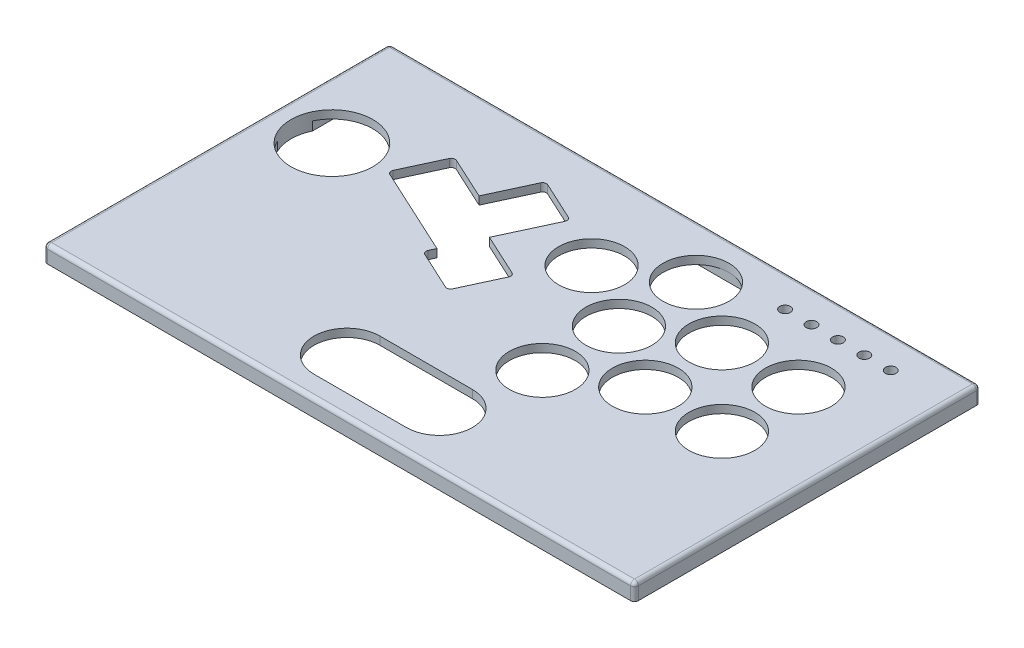
SolidWorks part; units mm, degrees
ref_plane "Front Plane" through (0, 0, 0) normal (0, 0, 1) x (1, 0, 0)
ref_plane "Top Plane" through (0, 0, 0) normal (0, 1, 0) x (1, 0, 0)
ref_plane "Right Plane" through (0, 0, 0) normal (1, 0, 0) x (0, 0, -1)
sketch "Button Cutouts" plane through (0, 0, 0) normal (0, 1, 0) x (1, 0, 0)
  line L0 (24.5, 61) -> (24.5, 32) construction
  line L1 (298.8548, 529.5585) -> (1494.2739, 529.5585) construction
  line L12 (-36.4482, 48.6137) -> (-28.8863, 64.9482) construction
  line L20 (49.5, 75) -> (49.5, 46) construction
  line L21 (78.5, 75) -> (78.5, 46) construction
  line L22 (17.5, 0) -> (-17.5, 0) construction
  line L28 (-36.4482, 48.6137) -> (-20.1137, 41.0518) construction
  line L29 (17.5, -12.5) -> (-17.5, -12.5)
  line L30 (17.5, 12.5) -> (-17.5, 12.5)
  line L31 (24.6803, 89.9994) -> (49.5, 75) construction
  line L32 (24.6803, 89.9994) -> (24.5, 61) construction
  line L33 (-0.5241, 75.6559) -> (24.6803, 89.9994) construction
  line L34 (-0.5241, 75.6559) -> (24.5, 61) construction
  line L48 (-28.8863, 64.9482) -> (-12.5518, 57.3863) construction
  line L49 (-20.1137, 41.0518) -> (-12.5518, 57.3863) construction
  line L50 (-36.4482, 48.6137) -> (-12.5518, 57.3863) construction
  line L51 (-28.8863, 64.9482) -> (-20.1137, 41.0518) construction
  line L52 (-35.7207, 52.6847) -> (-28.1587, 69.0192) construction
  line L53 (-35.7207, 52.6847) -> (-52.0552, 60.2467) construction
  line L54 (-28.1587, 69.0192) -> (-44.4932, 76.5812) construction
  line L55 (-52.0552, 60.2467) -> (-44.4932, 76.5812) construction
  line L56 (-35.7207, 52.6847) -> (-44.4932, 76.5812) construction
  line L57 (-28.1587, 69.0192) -> (-52.0552, 60.2467) construction
  line L58 (-69.3426, 68.2497) -> (-61.7806, 84.5842) construction
  line L59 (-69.3426, 68.2497) -> (-53.008, 60.6878) construction
  line L60 (-61.7806, 84.5842) -> (-45.4461, 77.0223) construction
  line L61 (-53.008, 60.6878) -> (-45.4461, 77.0223) construction
  line L62 (-69.3426, 68.2497) -> (-45.4461, 77.0223) construction
  line L63 (-61.7806, 84.5842) -> (-53.008, 60.6878) construction
  line L64 (-40.107, 64.633) -> (-22.8196, 56.6299) construction
  line L65 (-40.107, 64.633) -> (-57.3943, 72.636) construction
  line L66 (-44.0521, 77.534) -> (-36.4902, 93.8686) construction
  line L67 (-44.0521, 77.534) -> (-27.7176, 69.9721) construction
  line L68 (-36.4902, 93.8686) -> (-20.1557, 86.3066) construction
  line L69 (-27.7176, 69.9721) -> (-20.1557, 86.3066) construction
  line L70 (-44.0521, 77.534) -> (-20.1557, 86.3066) construction
  line L71 (-36.4902, 93.8686) -> (-27.7176, 69.9721) construction
  line L72 (-40.107, 64.633) -> (-32.1039, 81.9203) construction
  line L73 (-24.5, 53) -> (-22.8196, 56.6299) construction
  line L74 (-57.3943, 72.636) -> (-65.3974, 55.3486) construction
  line L75 (-65.3974, 55.3486) -> (-89.8992, 66.6915) construction
  line L76 (-70.0064, 68.006) -> (-62.0243, 85.248)
  line L77 (-62.0243, 85.248) -> (-44.7369, 77.245)
  line L78 (-44.7369, 77.245) -> (-36.7339, 94.5324)
  line L79 (-36.7339, 94.5324) -> (-19.4919, 86.5503)
  line L80 (-19.4919, 86.5503) -> (-29.1754, 65.633)
  line L81 (-29.1754, 65.633) -> (-11.888, 57.63)
  line L82 (-11.888, 57.63) -> (-19.87, 40.388)
  line L83 (-19.87, 40.388) -> (-37.112, 48.37)
  line L84 (-37.112, 48.37) -> (-35.4316, 51.9999)
  line L85 (-35.4316, 51.9999) -> (-70.0064, 68.006)
  line L86 (-65.5616, 76.417) -> (-66.0153, 76.627) construction
  line L87 (-28.1129, 90.5413) -> (-28.3229, 90.0876) construction
  line L88 (-16.3327, 49.219) -> (-15.879, 49.009) construction
  circle A0 centre (24.5, 32) radius 12.5
  circle A1 centre (24.5, 61) radius 12.5
  circle A2 centre (49.5, 46) radius 12.5
  circle A3 centre (49.5, 75) radius 12.5
  circle A4 centre (78.5, 75) radius 12.5
  circle A5 centre (78.5, 46) radius 12.5
  arc A8 (17.5, -12.5) -> (17.5, 12.5) centre (17.5, 0) ccw
  arc A9 (-17.5, 12.5) -> (-17.5, -12.5) centre (-17.5, 0) ccw
  circle A10 centre (-89.8992, 66.6915) radius 15.5
  circle A11 centre (24.6803, 89.9994) radius 12.5
  circle A12 centre (-0.5241, 75.6559) radius 12.5
  point P1 (-24.5, 53)
  point P5 (-40.107, 64.633)
  point P6 (-57.3943, 72.636)
  point P37 (0, 0)
  point P45 (-32.1039, 81.9203)
  point P54 (-30, 0)
  point P55 (30, 0)
  dimension "D2" = 25
  dimension "D12" = 12.5
  dimension "D18" = 31
  dimension "D1" = 29
  dimension "D3" = 25
  dimension "D4" = 29
  dimension "D5" = 14
  dimension "D6" = 18
  dimension "D7" = 19.05
  dimension "D8" = 53
  dimension "D9" = 7
  dimension "D10" = 4
  dimension "D11" = 27
  dimension "D13" = 32
  dimension "D14" = 7
  dimension "D15" = 19.05
  dimension "D16" = 0.5
  dimension "D17" = 60
  dimension "D19" = 0.5
  dimension "D20" = 0.5
  dimension "D21" = 29
  dimension "D22" = 29
  dimension "D23" = 0.5
  dimension "D24" = 0.5
sketch "Sketch2" plane through (0, 0, 0) normal (0, 1, 0) x (1, 0, 0)
  line L0 (-105.3992, 66.6915) -> (-111.8992, 66.6915) construction
  line L1 (-111.8992, 110.4994) -> (111.8992, 110.4994)
  line L2 (-111.8992, 110.4994) -> (-111.8992, -20.5)
  line L3 (-111.8992, -20.5) -> (111.8992, -20.5)
  line L4 (111.8992, 110.4994) -> (111.8992, -20.5)
  line L5 (24.6803, 102.4994) -> (24.6803, 110.4994) construction
  line L6 (0, -12.5) -> (0, -20.5) construction
  line L7 (17.5, -12.5) -> (-17.5, -12.5) construction
  circle A0 centre (-89.8992, 66.6915) radius 15.5 construction
  circle A2 centre (24.6803, 89.9994) radius 12.5 construction
  point P4 (0, -20.5)
  point P6 (-96.957, 37.95)
  point P7 (-108.1216, 67.9519)
  point P22 (116.1216, 110.4994)
  point P23 (0, 0)
  dimension "D2" = 6.5
  dimension "D1" = 8
  dimension "D3" = 8
extrude "top plate" add sketch "Sketch2" along normal blind 6.35
extrude "primary button cutouts" cut sketch "Button Cutouts" along normal up to next
fillet "Fillet1" radius 1.5 7 edges at (-19.4919, 3.175, -86.5503) (-11.888, 3.175, -57.63) (-19.87, 3.175, -40.388) (-37.112, 3.175, -48.37) (-70.0064, 3.175, -68.006) (-62.0243, 3.175, -85.248) (-36.7339, 3.175, -94.5324)
sketch "Sketch3" plane through (0, 6.35, 0) normal (0, 1, 0) x (1, 0, 0)
  circle A0 centre (50.4737, 97.9764) radius 2
  circle A1 centre (60.4737, 97.9764) radius 2
  circle A2 centre (70.4737, 97.9764) radius 2
  circle A3 centre (80.4737, 97.9764) radius 2
  circle A4 centre (90.4737, 97.9764) radius 2
  point P2 (59.2389, 98.5911)
  point P3 (52.2391, 98.3336)
  point P12 (50.4737, 97.9764)
  dimension "D2" = 4
  dimension "D1" = 5
extrude "extra buttons" cut sketch "Sketch3" against normal up to next
sketch "Sketch4" plane through (0, 0, 0) normal (0, -1, 0) x (1, 0, 0)
  line L0 (111.8992, 20.5) -> (111.8992, -110.4994) construction
  line L1 (-103.8992, 12.5) -> (103.8992, 12.5)
  line L2 (-103.8992, 12.5) -> (-103.8992, -102.4994)
  line L3 (-103.8992, -102.4994) -> (103.8992, -102.4994)
  line L4 (103.8992, 12.5) -> (103.8992, -102.4994)
  line L5 (-111.8992, 20.5) -> (111.8992, 20.5) construction
  line L6 (111.8992, -110.4994) -> (-111.8992, -110.4994) construction
  line L7 (-111.8992, -110.4994) -> (-111.8992, 20.5) construction
  dimension "D1" = 8
  dimension "D2" = 8
  dimension "D3" = 8
  dimension "D4" = 8
extrude "Cut-Extrude2" cut sketch "Sketch4" against normal blind 3.3
sketch "Sketch5" plane through (0, 0, 0) normal (0, -1, 0) x (1, 0, 0)
  line L0 (111.8992, -110.4994) -> (-111.8992, -110.4994) construction
  line L1 (-7, -110.4994) -> (7, -110.4994)
  line L2 (-7, -110.4994) -> (-7, -102.4994)
  line L3 (-7, -102.4994) -> (7, -102.4994)
  line L4 (7, -110.4994) -> (7, -102.4994)
  line L5 (-103.8992, -102.4994) -> (24.6803, -102.4994) construction
  point P8 (0, -102.4994)
  dimension "D1" = 14
extrude "Cut-Extrude3" cut sketch "Sketch5" against normal up to surface (3.3 mm away) up to face at (-0.5241, 3.3, -88.1559)
sketch "Sketch6" plane through (0, 0, 0) normal (0, -1, 0) x (1, 0, 0)
  line L0 (111.8992, 20.5) -> (111.8992, -110.4994) construction
  line L1 (-111.8992, 20.5) -> (111.8992, 20.5) construction
  line L2 (111.8992, -110.4994) -> (7, -110.4994) construction
  line L3 (-111.8992, -110.4994) -> (-111.8992, 20.5) construction
  line L4 (7, -102.4994) -> (7, -110.4994) construction
  line L5 (-7, -110.4994) -> (-7, -102.4994) construction
  point P0 (107.8992, 16.5)
  point P1 (107.8992, -106.4994)
  point P2 (-107.8992, -106.4994)
  point P3 (-107.8992, 16.5)
  point P4 (0, 16.327)
  point P5 (11, -106.4994)
  point P6 (-11, -106.4994)
  point P12 (0, 0)
  point P18 (-83.7838, 48.1675)
  point P19 (0, 0)
  point P20 (0, 0)
  point P21 (0, 0)
  point P22 (0, 0)
  point P23 (0, 0)
  point P24 (0, 0)
  point P25 (0, 0)
  point P30 (0, 0)
  dimension "D1" = 4
  dimension "D2" = 4
  dimension "D3" = 4
  dimension "D4" = 4
  dimension "D5" = 4
  dimension "D6" = 4
hole_wizard "M3x0.5 Tapped Hole1" positions "3DSketch1" profile "Sketch7" tap size "M3x0.5" standard "ANSI Metric"
sketch3d "3DSketch1"
  point P0 (-107.8992, 0, -106.4994)
  point P3 (-11, 0, -106.4994)
  point P6 (11, 0, -106.4994)
  point P9 (107.8992, 0, -106.4994)
  point P12 (107.8992, 0, 16.5)
  point P15 (0, 0, 16.327)
  point P18 (-107.8992, 0, 16.5)
cosmetic thread "Hole Thread1" parameters "D1"=2.5, "D2"=3
cosmetic thread "Hole Thread2" parameters "D1"=2.5, "D2"=3
cosmetic thread "Hole Thread3" parameters "D1"=2.5, "D2"=3
cosmetic thread "Hole Thread4" parameters "D1"=2.5, "D2"=3
cosmetic thread "Hole Thread5" parameters "D1"=2.5, "D2"=3
cosmetic thread "Hole Thread6" parameters "D1"=2.5, "D2"=3
cosmetic thread "Hole Thread7" parameters "D1"=2.5, "D2"=3
sketch "Sketch7" plane through (-107.8992, 0, -106.4994) normal (1, 0, 0) x (0, 0, -1)
  line L0 (0, 0) -> (0, 3.2511)
  line L1 (0, 3.2511) -> (1.25, 2.5)
  line L2 (1.25, 2.5) -> (1.25, 0)
  line L5 (1.25, 0) -> (0, 0)
  line L10 (0, 3.2511) -> (-1.25, 2.5) construction
  line L11 (0, -6.35) -> (0, 107.95) construction
  dimension "Tap Drill Dia." = 2.5
  dimension "Tap Drill Depth" = 2.5
  dimension "Drill Angle" = 118
fillet "Fillet2" radius 1.5 8 edges at (111.8992, 3.175, -110.4994) (-111.8992, 3.175, -110.4994) (-111.8992, 3.175, 20.5) (111.8992, 3.175, 20.5) (111.8992, 6.35, -44.9997) (0, 6.35, -110.4994) (0, 6.35, 20.5) (-111.8992, 6.35, -44.9997)
